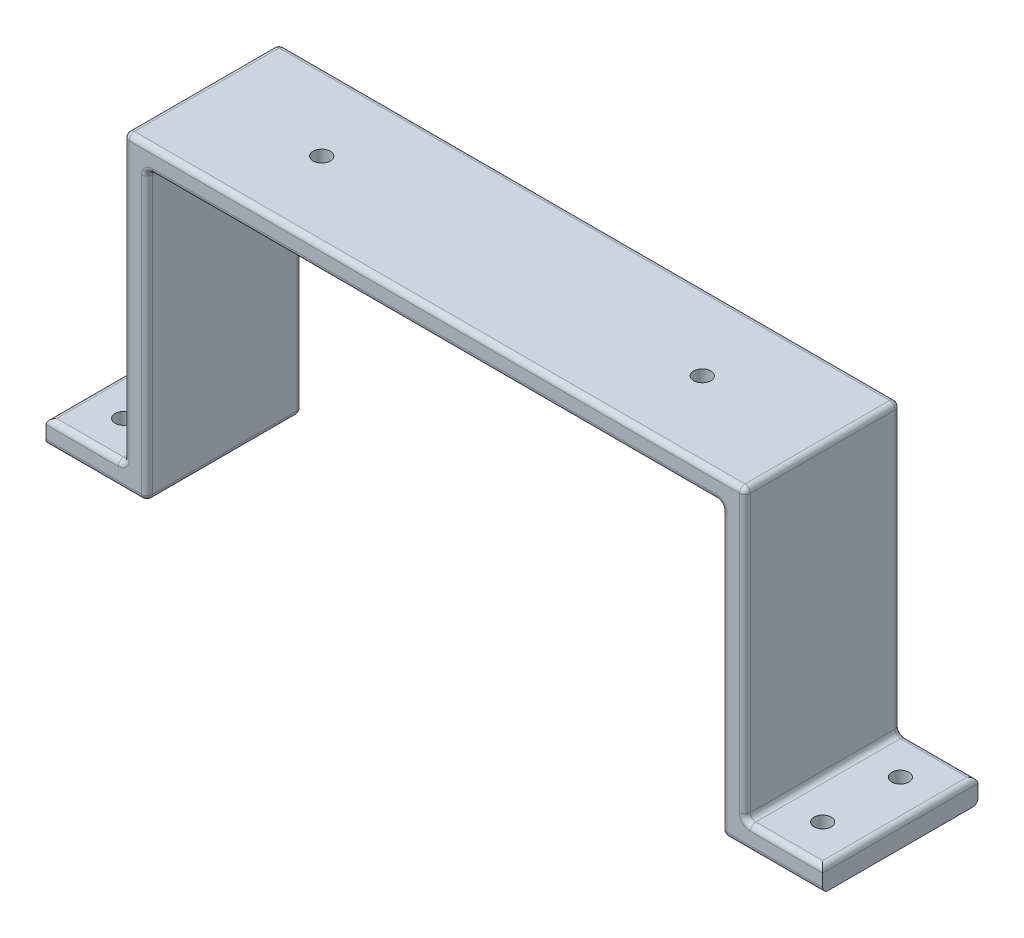
SolidWorks part; units mm, degrees
ref_plane "前视基准面" through (0, 0, 0) normal (0, 0, 1) x (1, 0, 0)
ref_plane "上视基准面" through (0, 0, 0) normal (0, 1, 0) x (1, 0, 0)
ref_plane "右视基准面" through (0, 0, 0) normal (1, 0, 0) x (0, 0, -1)
other "Configuration Table"
sketch "草图1" plane through (0, 0, 0) normal (0, 1, 0) x (1, 0, 0)
  line L0 (0, -55) -> (0, 55) construction
  line L1 (-5, 10) -> (5, 10)
  line L2 (-5, 10) -> (-5, -10)
  line L3 (-5, -10) -> (5, -10)
  line L4 (5, 10) -> (5, -10)
  line L5 (-55, 0) -> (55, 0) construction
  dimension "D1" = 20
  dimension "D2" = 10
  dimension "D3" = 5
  dimension "D4" = 10
extrude "凸台-拉伸1" add sketch "草图1" along normal blind 3
hole_wizard "Ø2.2 (2.2) 直径孔1" positions "草图2" profile "草图3" hole size "Ø2.2" standard "ANSI Metric" end condition up to next
sketch "草图2" plane through (0, 3, 0) normal (0, 1, 0) x (1, 0, 0)
  line L0 (0, -1.65) -> (0, 1.65) construction
  line L1 (5, 10) -> (-5, 10) construction
  point P0 (0, 5)
  point P4 (0, -5)
  dimension "D1" = 5
  dimension "D2" = 10
sketch "草图3" plane through (0, 3, -5) normal (1, 0, 0) x (0, 0, 1)
  line L0 (0, 0) -> (0, 3)
  line L1 (0, 3) -> (1.1, 3)
  line L2 (1.1, 3) -> (1.1, 0)
  line L5 (1.1, 0) -> (0, 0)
  line L11 (0, -6.35) -> (0, 107.95) construction
  dimension "通孔孔直径" = 2.2
  dimension "通孔孔深度" = 3
sketch "草图5" plane through (5, 0, 0) normal (1, 0, 0) x (0, 0, -1)
  line L1 (-10, 0) -> (10, 0)
  line L2 (-10, 0) -> (-10, 40)
  line L3 (-10, 40) -> (10, 40)
  line L4 (10, 0) -> (10, 40)
  dimension "D1" = 40
  dimension "D2" = 20
extrude "凸台-拉伸2" add sketch "草图5" along normal blind 80
ref_plane "基准面1" through (45, 0, 0) normal (-1, 0, 0) x (0, 0, 1)
mirror "镜向1" about plane through (45, 0, 0) normal (-1, 0, 0) of "Ø2.2 (2.2) 直径孔1", "凸台-拉伸1"
sketch "草图6" plane through (0, 0, 10) normal (0, 0, 1) x (1, 0, 0)
  line L0 (11, 0) -> (-11, 0) construction
  line L1 (8, 0) -> (82, 0)
  line L2 (8, 0) -> (8, 37)
  line L3 (8, 37) -> (82, 37)
  line L4 (82, 0) -> (82, 37)
  line L5 (5, 40) -> (5, 3) construction
  line L6 (85, 40) -> (85, 3) construction
  line L7 (85, 40) -> (5, 40) construction
  dimension "D1" = 3
  dimension "D2" = 3
  dimension "D3" = 3
extrude "切除-拉伸1" cut sketch "草图6" against normal up to next
hole_wizard "Ø2.2 (2.2) 直径孔2" positions "草图9" profile "草图10" hole size "Ø2.2" standard "ANSI Metric" end condition up to next
sketch "草图9" plane through (0, 40, 0) normal (0, 1, 0) x (1, 0, 0)
  line L0 (-22, 0) -> (22, 0) construction
  line L1 (45, 11) -> (45, -11) construction
  point P0 (20.5, 0)
  point P4 (69.5, 0)
  dimension "D1" = 49
  dimension "D2" = 24.5
sketch "草图10" plane through (20.5, 40, 0) normal (1, 0, 0) x (0, 0, 1)
  line L0 (0, 0) -> (0, 3)
  line L1 (0, 3) -> (1.1, 3)
  line L2 (1.1, 3) -> (1.1, 0)
  line L5 (1.1, 0) -> (0, 0)
  line L11 (0, -6.35) -> (0, 107.95) construction
  dimension "通孔孔直径" = 2.2
  dimension "通孔孔深度" = 3
fillet "圆角1" radius 0.7 30 edges at (82, 18.5, -10) (0, 3, 10) (8, 37, 0) (82, 37, 0) (82, 0, 0) (88.5, 0, -10) (1.5, 0, -10) (8, 18.5, -10) (45, 37, -10) (5, 21.5, -10) (5, 3, 0) (45, 40, -10) (85, 40, 0) (85, 21.5, -10) (90, 3, -10) (90, 3, 10) (85, 3, 0) (95, 3, 0) (85, 21.5, 10) (88.5, 0, 10) (82, 18.5, 10) (8, 0, 0) (1.5, 0, 10) (0, 3, -10) (-5, 3, 0) (8, 18.5, 10) (45, 37, 10) (45, 40, 10) (5, 40, 0) (5, 21.5, 10)
